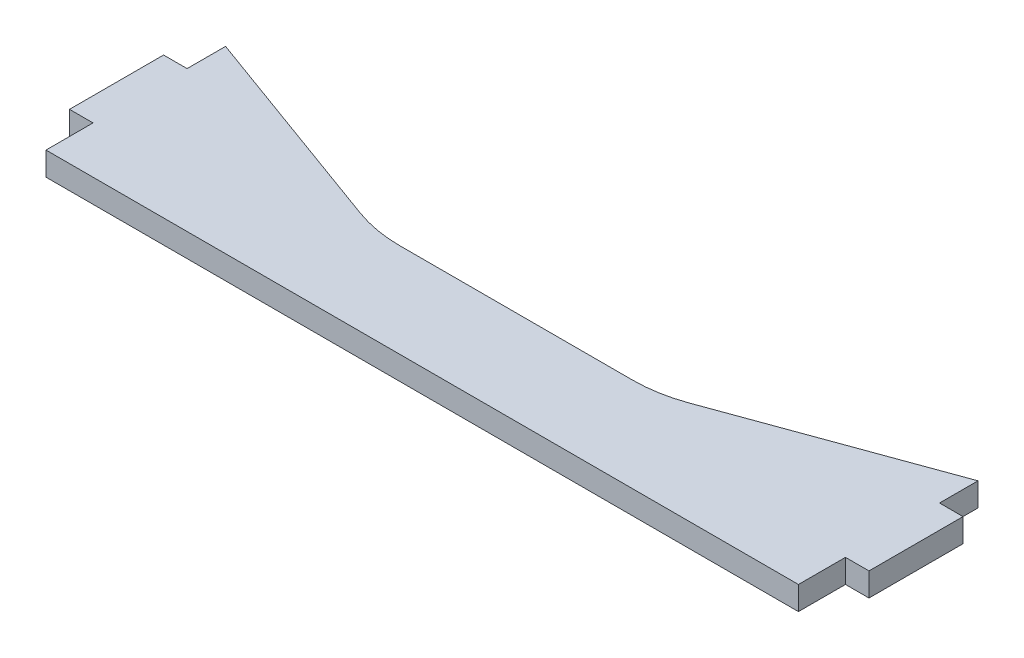
SolidWorks part; units mm, degrees
ref_plane "정면" through (0, 0, 0) normal (0, 0, 1) x (1, 0, 0)
ref_plane "윗면" through (0, 0, 0) normal (0, 1, 0) x (1, 0, 0)
ref_plane "우측면" through (0, 0, 0) normal (1, 0, 0) x (0, 0, -1)
sketch "스케치1" plane through (0, 0, 0) normal (0, 1, 0) x (1, 0, 0)
  line L1 (0, 0) -> (170, 0)
  line L2 (0, 0) -> (0, 20)
  line L3 (0, 20) -> (170, 20)
  line L4 (170, 0) -> (170, 20)
  dimension "D1" = 170
  dimension "D2" = 20
extrude "보스-돌출1" add sketch "스케치1" along normal blind 5
sketch "스케치2" plane through (0, 5, 0) normal (0, 1, 0) x (1, 0, 0)
  line L0 (170, 20) -> (170, 40)
  line L1 (170, 40) -> (115, 20)
  line L2 (115, 20) -> (170, 20)
  line L3 (170, 20) -> (169.9716, 19.9021)
  line L4 (0, 20) -> (55, 20)
  line L5 (170, 20) -> (0, 20) construction
  line L6 (55, 20) -> (0, 40)
  line L7 (0, 40) -> (0, 20)
  line M4 (170, 20) -> (0, 20)
  dimension "D1" = 55
  dimension "D2" = 55
  dimension "D3" = 20
  dimension "D4" = 20
extrude "보스-돌출2" add sketch "스케치2" against normal blind 5 contours L6 L7 M4 | L0 L1 M4
fillet "필렛1" radius 30 2 edges at (115, 2.5, -20)
sketch "스케치3" plane through (0, 0, 0) normal (0, -1, 0) x (1, 0, 0)
  line L1 (165, -10) -> (170, -10)
  line L2 (165, -10) -> (165, 0)
  line L3 (165, 0) -> (170, 0)
  line L4 (170, -10) -> (170, 0)
  line L5 (165, -30) -> (170, -30)
  line L6 (165, -30) -> (165, -40)
  line L7 (165, -40) -> (170, -40)
  line L8 (170, -30) -> (170, -40)
  line L9 (5, -30) -> (0, -30)
  line L10 (5, -30) -> (5, -40)
  line L11 (5, -40) -> (0, -40)
  line L12 (0, -30) -> (0, -40)
  line L13 (5, -10) -> (0, -10)
  line L14 (5, -10) -> (5, 0)
  line L15 (5, 0) -> (0, 0)
  line L16 (0, -10) -> (0, 0)
extrude "컷-돌출1" cut sketch "스케치3" against normal blind 10
